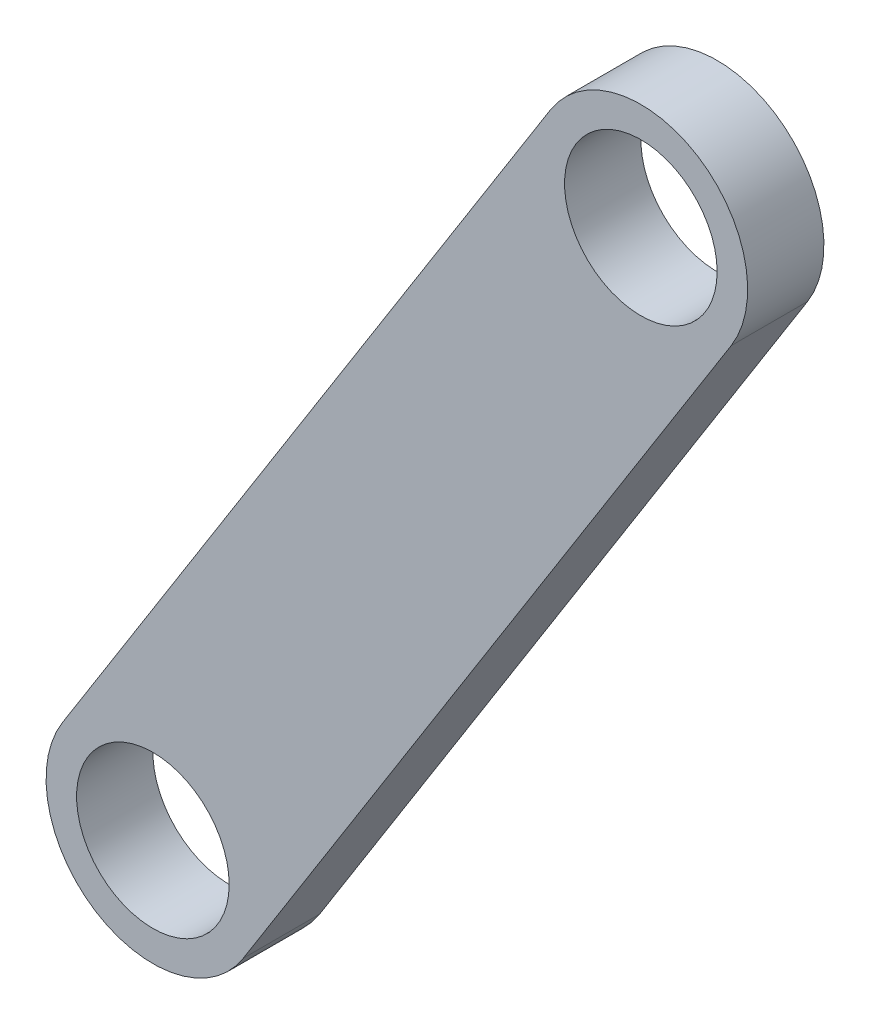
SolidWorks part; units mm, degrees
ref_plane "Front Plane" through (0, 0, 0) normal (0, 0, 1) x (1, 0, 0)
ref_plane "Top Plane" through (0, 0, 0) normal (0, 1, 0) x (1, 0, 0)
ref_plane "Right Plane" through (0, 0, 0) normal (1, 0, 0) x (0, 0, -1)
sketch "Sketch1" plane through (0, 0, 0) normal (0, 0, 1) x (1, 0, 0)
  line L0 (0, 12) -> (31.9816, 62.7659) construction
  line L1 (-5.9227, 15.7312) -> (26.0589, 66.4971)
  line L2 (5.9227, 8.2688) -> (37.9043, 59.0347)
  arc A0 (-5.9227, 15.7312) -> (5.9227, 8.2688) centre (0, 12) ccw
  arc A1 (37.9043, 59.0347) -> (26.0589, 66.4971) centre (31.9816, 62.7659) ccw
  circle A2 centre (0, 12) radius 5
  circle A3 centre (31.9816, 62.7659) radius 5
  point P3 (15.9908, 37.383)
  dimension "D2" = 7
  dimension "D3" = 10
  dimension "D1" = 60
extrude "Boss-Extrude1" add sketch "Sketch1" along normal blind 5
